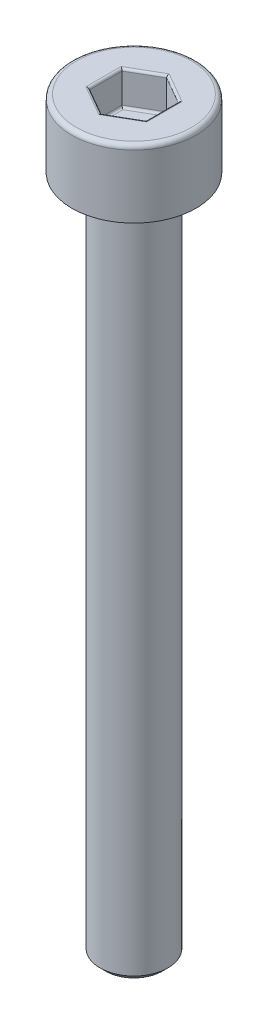
SolidWorks part; units mm, degrees
ref_plane "Front Plane" through (0, 0, 0) normal (0, 0, 1) x (1, 0, 0)
ref_plane "Top Plane" through (0, 0, 0) normal (0, 1, 0) x (1, 0, 0)
ref_plane "Right Plane" through (0, 0, 0) normal (1, 0, 0) x (0, 0, -1)
sketch "Sketch1" plane through (0, 0, 0) normal (0, 0, 1) x (1, 0, 0)
  line L0 (0, 0) -> (0, -47.0967) construction
  line L1 (0, -33) -> (-1.5, -33)
  line L2 (-1.5, -33) -> (-1.5, -3)
  line L3 (-1.5, -3) -> (-2.75, -3)
  line L4 (-2.75, -3) -> (-2.75, 0)
  line L5 (-2.75, 0) -> (0, 0)
  line L6 (0, 0) -> (0, -33)
  dimension "d" = 3
  dimension "l" = 33
  dimension "k" = 3
  dimension "dk" = 5.5
revolve "Revolve1" add sketch "Sketch1" angle 360 about L0
chamfer "Chamfer1" distance 0.25 angle 45 2 edges at (0, -3, 1.5) (0, -33, 1.5)
fillet "Fillet1" radius 0.2 1 edges at (0, 0, 2.75)
sketch "Sketch2" plane through (0, 0, 0) normal (0, 1, 0) x (1, 0, 0)
  line L1 (0, 1.4434) -> (-1.25, 0.7217)
  line L2 (-1.25, 0.7217) -> (-1.25, -0.7217)
  line L3 (-1.25, -0.7217) -> (0, -1.4434)
  line L4 (0, -1.4434) -> (1.25, -0.7217)
  line L5 (1.25, -0.7217) -> (1.25, 0.7217)
  line L6 (1.25, 0.7217) -> (0, 1.4434)
  circle A0 centre (0, 0) radius 1.25 construction
  dimension "s" = 2.5
extrude "Cut-Extrude1" cut sketch "Sketch2" against normal blind 1.5
fillet "Fillet2" radius 0.1 12 edges at (-0.625, 0, -1.0825) (-1.25, 0, 0) (-0.625, 0, 1.0825) (0.625, 0, 1.0825) (1.25, 0, 0) (0.625, 0, -1.0825) (1.25, -1.5, 0) (0.625, -1.5, 1.0825) (-0.625, -1.5, 1.0825) (-1.25, -1.5, 0) (-0.625, -1.5, -1.0825) (0.625, -1.5, -1.0825)
